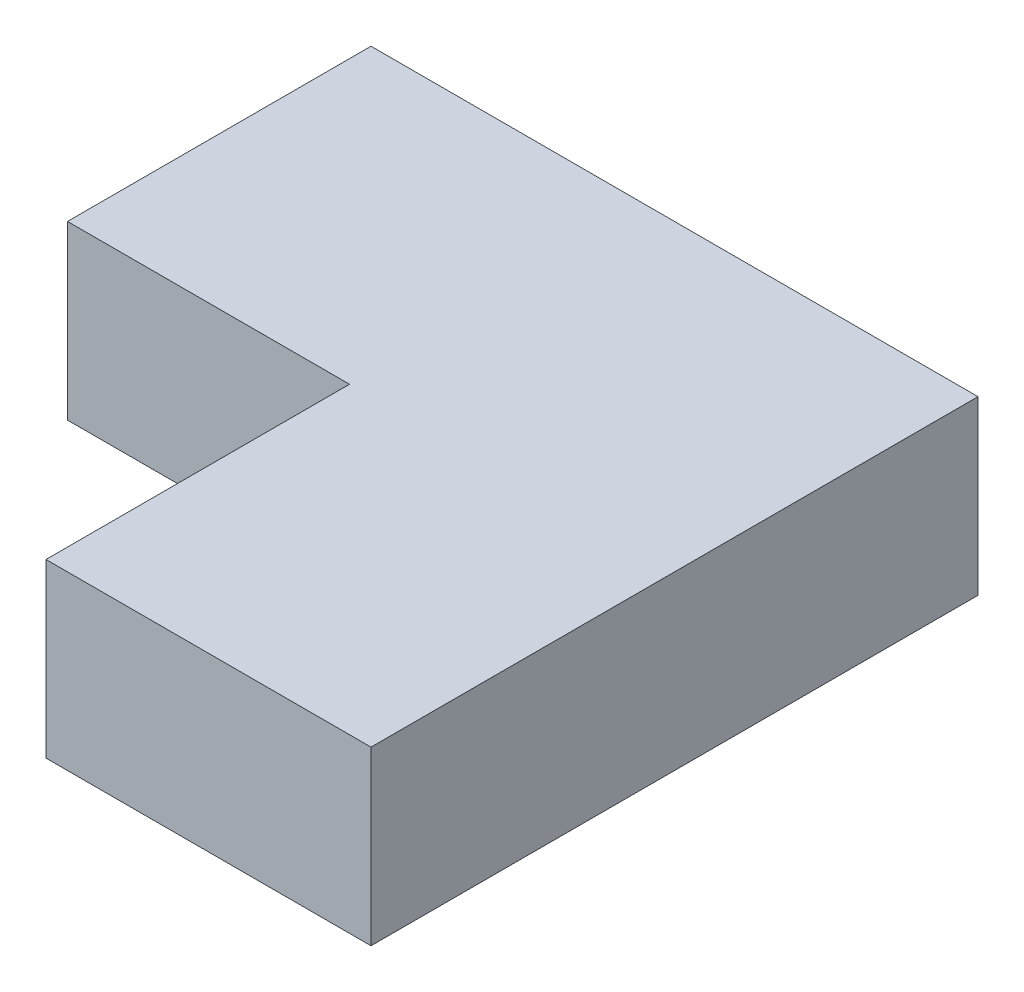
SolidWorks part; units mm, degrees
ref_plane "Front Plane" through (0, 0, 0) normal (0, 0, 1) x (1, 0, 0)
ref_plane "Top Plane" through (0, 0, 0) normal (0, 1, 0) x (1, 0, 0)
ref_plane "Right Plane" through (0, 0, 0) normal (1, 0, 0) x (0, 0, -1)
sketch "Sketch1" plane through (0, 0, 0) normal (0, 1, 0) x (1, 0, 0)
  line L1 (-89.0948, -55.3407) -> (-43.1387, -55.3407)
  line L2 (-89.0948, -55.3407) -> (-89.0948, 5.4186)
  line L3 (-89.0948, 5.4186) -> (-43.1387, 5.4186)
  line L4 (-43.1387, -55.3407) -> (-43.1387, 5.4186)
  line L5 (-89.0948, -55.3407) -> (-43.1387, 5.4186) construction
  line L6 (-89.0948, 5.4186) -> (-43.1387, -55.3407) construction
  point P4 (-66.1167, -24.961)
extrude "Boss-Extrude1" add sketch "Sketch1" along normal blind 4.8
sketch "Sketch2" plane through (0, 4.8, 0) normal (0, 1, 0) x (1, 0, 0)
  line L0 (-52.2054, -55.3407) -> (-43.1387, -55.3407) construction
  line L1 (-89.0948, -55.3407) -> (-52.2054, -55.3407)
  line L2 (-89.0948, -55.3407) -> (-89.0948, -3.048)
  line L3 (-89.0948, -3.048) -> (-52.2054, -3.048)
  line L4 (-52.2054, -55.3407) -> (-52.2054, -3.048)
  line L5 (-89.0948, -55.3407) -> (-52.2054, -3.048) construction
  line L6 (-89.0948, -3.048) -> (-52.2054, -55.3407) construction
  line L8 (-43.1387, 5.4186) -> (-89.0948, 5.4186) construction
  point P4 (-70.6501, -29.1944)
  dimension "D1" = 8.4667
  dimension "D2" = 9.0667
extrude "Cut-Extrude1" cut sketch "Sketch2" against normal through all
sketch "Sketch3" plane through (0, 4.8, 0) normal (0, 1, 0) x (1, 0, 0)
  line L0 (-43.1387, 5.4186) -> (-43.1387, -11.5147) construction
  line L3 (-43.1387, -55.3407) -> (-43.1387, 5.4186) construction
  line L4 (-52.2054, -55.3407) -> (-52.2054, -3.048) construction
  line L5 (-43.1387, -55.3407) -> (-52.2054, -55.3407)
  line L6 (-43.1387, -55.3407) -> (-43.1387, -11.5147)
  line L7 (-43.1387, -11.5147) -> (-52.2054, -11.5147)
  line L8 (-52.2054, -55.3407) -> (-52.2054, -11.5147)
  line L9 (-43.1387, -55.3407) -> (-52.2054, -11.5147) construction
  line L10 (-43.1387, -11.5147) -> (-52.2054, -55.3407) construction
  point P7 (-47.672, -33.4277)
  dimension "D1" = 16.9333
extrude "Cut-Extrude3" cut sketch "Sketch3" against normal through all contours L6 L5 L8 L7
sketch "Sketch4" plane through (0, 4.8, 0) normal (0, 1, 0) x (1, 0, 0)
  line L5 (-43.1387, 5.4186) -> (-60.072, 5.4186) construction
  line L6 (-43.1387, 5.4186) -> (-89.0948, 5.4186) construction
  line L8 (-89.0948, 5.4186) -> (-89.0948, -3.048) construction
  line L9 (-89.0948, 5.4186) -> (-60.072, 5.4186)
  line L10 (-89.0948, 5.4186) -> (-89.0948, -3.048)
  line L11 (-89.0948, -3.048) -> (-60.072, -3.048)
  line L12 (-60.072, 5.4186) -> (-60.072, -3.048)
  line L13 (-89.0948, 5.4186) -> (-60.072, -3.048) construction
  line L14 (-89.0948, -3.048) -> (-60.072, 5.4186) construction
  line L15 (-52.2054, -3.048) -> (-89.0948, -3.048) construction
  point P7 (-74.5834, 1.1853)
  dimension "D1" = 16.9333
extrude "Cut-Extrude4" cut sketch "Sketch4" against normal through all
equation "\"MDF\"= 4.8mm"
equation "\"Foamcore\"= 4.6mm"
equation "\"PCB\" = 1.6mm"
equation "\"GMaterial\"= \"MDF\""
equation "\"D1@Boss-Extrude1\"=\"GMaterial\""
equation "\"BaseWidth\" = 10in"
equation "\"SkidLength\" = 1in"
equation "\"SkidClearance\" = 0.4in"
equation "\"MotorMountLength\" = 2in"
equation "\"MotorMountWidth\" = \"GMaterial\""
equation "\"MotorMountHeight\" = 2.25in"
equation "\"UnoStackWidth\" = 77.4mm"
equation "\"UnoStackLength\" = 79.8mm"
equation "\"UnoStackHeight\" = 34.2mm"
equation "\"TallHexRiserHeight\" = 22.2mm"
equation "\"PingPongBallSize\" = 40mm"
equation "\"BarrelLength\" = 9in"
equation "\"BarrelSize\" = \"PingPongBallSize\""
equation "\"PlatformLength\" = 4in"
equation "\"PlatformWidth\" = 6in"
equation "\"WheelWidth\"= 26mm"
equation "\"WheelDiameter\"=2.99213"
equation "\"ServoMountHeight\"=2.49223"
equation "\"ServoGearHeight\" = 0.95330261in"
equation "\"ServoMountLength\"= 1.53774"
equation "\"PivotHoleRadius\"= 0.616358"
equation "\"PlatformMountHeight\" = 3.19"
equation "\"TensionOffSet\"= .3mm"
equation "\"MotorMountWedge\"=0.333333"
equation "\"D1@Sketch2\"=\"MotorMountWedge\""
equation "\"D2@Sketch2\"=\"TensionOffSet\"*2+1/3"
